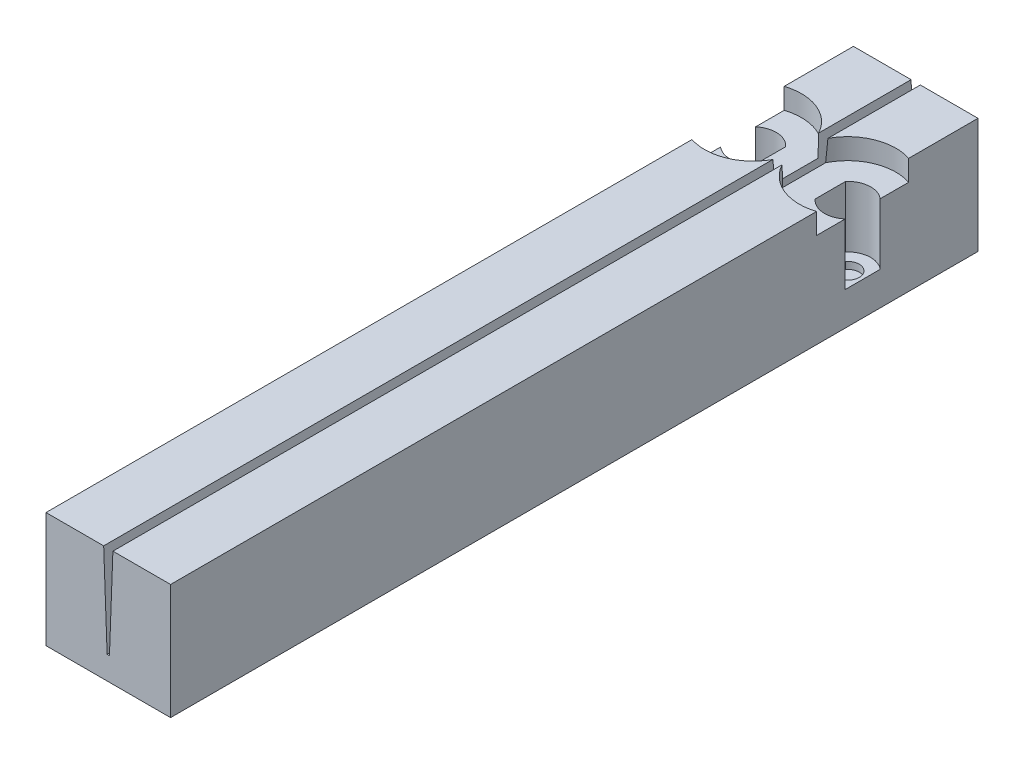
SolidWorks part; units mm, degrees
ref_plane "Front Plane" through (0, 0, 0) normal (0, 0, 1) x (1, 0, 0)
ref_plane "Top Plane" through (0, 0, 0) normal (0, 1, 0) x (1, 0, 0)
ref_plane "Right Plane" through (0, 0, 0) normal (1, 0, 0) x (0, 0, -1)
sketch "Sketch1" plane through (0, 0, 0) normal (0, 1, 0) x (1, 0, 0)
  line L1 (-27, -175) -> (27, -175)
  line L2 (-27, -175) -> (-27, 175)
  line L3 (-27, 175) -> (27, 175)
  line L4 (27, -175) -> (27, 175)
  line L5 (-27, -175) -> (27, 175) construction
  line L6 (-27, 175) -> (27, -175) construction
  point P0 (0, 0)
  dimension "D1" = 350
  dimension "D2" = 54
extrude "Boss-Extrude1" add sketch "Sketch1" along normal blind 50
sketch "Sketch3" plane through (0, 0, 175) normal (0, 0, 1) x (1, 0, 0)
  line L0 (0.5, 50) -> (0.5, 10) construction
  line L1 (-27, 50) -> (27, 50) construction
  line L2 (-27, 0) -> (27, 0) construction
  line L3 (-27, 50) -> (-27, 0) construction
  line L4 (-0.5, 10) -> (-0.5, 50) construction
  line L5 (27, 50) -> (27, 0) construction
  line L11 (-0.5, 10) -> (-2, 50)
  line L13 (2, 50) -> (0.5, 10)
  line L14 (-0.5, 10) -> (0.5, 10)
  line L15 (-2, 50) -> (2, 50)
  dimension "D1" = 10
  dimension "D2" = 27.5
  dimension "D3" = 10
  dimension "D4" = 27.5
  dimension "D5" = 4
extrude "Cut-Extrude2" cut sketch "Sketch3" against normal through all
sketch "Sketch7" plane through (0, 50, 0) normal (0, 1, 0) x (1, 0, 0)
  line L3 (27, 175) -> (2, 175) construction
  line L5 (-0.5, 175) -> (-0.5, -175) construction
  circle A0 centre (20.5, 125) radius 10
  circle A1 centre (20.5, 125) radius 20 construction
  circle A2 centre (20.5, 125) radius 21
  dimension "D1" = 20
  dimension "D3" = 40
  dimension "D4" = 1
  dimension "D5" = 50
  dimension "D2" = 21
extrude "Cut-Extrude4" cut sketch "Sketch7" against normal blind 9
sketch "Sketch9" plane through (0, 50, 0) normal (0, 1, 0) x (1, 0, 0)
  line L0 (13, 131.6144) -> (13, 118.3856)
  circle A0 centre (20.5, 125) radius 10 construction
  arc A1 (13, 131.6144) -> (13, 118.3856) centre (20.5, 125) cw
  dimension "D1" = 20
  dimension "D2" = 7.5
extrude "Cut-Extrude5" cut sketch "Sketch9" against normal blind 35.5
sketch "Sketch10" plane through (0, 14.5, 0) normal (0, 1, 0) x (1, 0, 0)
  line L0 (16.5, 128) -> (16.5, 122)
  arc A1 (16.5, 128) -> (16.5, 122) centre (20.5, 125) cw
  dimension "D1" = 6
  dimension "D2" = 5
extrude "Cut-Extrude6" cut sketch "Sketch10" against normal blind 3
sketch "Sketch11" plane through (0, 50, 0) normal (0, 1, 0) x (1, 0, 0)
  line L0 (13, 131.6144) -> (13, 118.3856)
  arc A0 (13, 131.6144) -> (13, 118.3856) centre (20.5, 125) ccw
extrude "Cut-Extrude7" cut sketch "Sketch11" against normal blind 9
mirror "Mirror1" about plane through (0, 0, 0) normal (1, 0, 0) of "Cut-Extrude7", "Cut-Extrude4", "Cut-Extrude5", "Cut-Extrude6"
